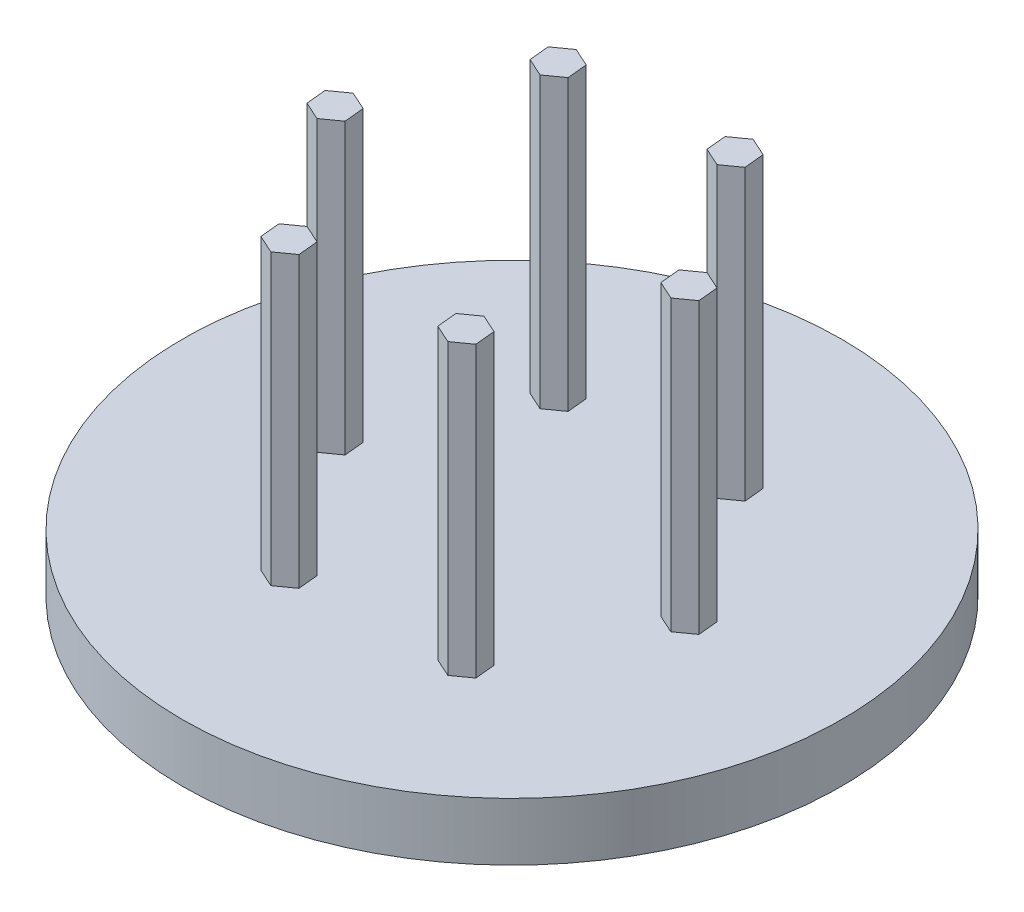
SolidWorks part; units mm, degrees
ref_plane "前视基准面" through (0, 0, 0) normal (0, 0, 1) x (1, 0, 0)
ref_plane "上视基准面" through (0, 0, 0) normal (0, 1, 0) x (1, 0, 0)
ref_plane "右视基准面" through (0, 0, 0) normal (1, 0, 0) x (0, 0, -1)
other "Configuration Table"
sketch "草图1" plane through (0, 0, 0) normal (0, 1, 0) x (1, 0, 0)
  line L0 (15.9541, 0.2119) -> (15.7851, 1.9437)
  line L1 (6.5472, 11.1786) -> (7.9625, 12.1908)
  line L2 (7.9625, 12.1908) -> (7.7935, 13.9226)
  line L3 (7.7935, 13.9226) -> (6.2093, 14.6422)
  line L4 (6.2093, 14.6422) -> (4.794, 13.63)
  line L5 (4.794, 13.63) -> (4.963, 11.8982)
  line L6 (4.963, 11.8982) -> (6.5472, 11.1786)
  line L7 (14.5388, -0.8003) -> (15.9541, 0.2119)
  line L8 (12.9546, -0.0807) -> (14.5388, -0.8003)
  line L9 (12.7856, 1.651) -> (12.9546, -0.0807)
  line L10 (14.2009, 2.6632) -> (12.7856, 1.651)
  line L11 (15.7851, 1.9437) -> (14.2009, 2.6632)
  line L12 (8.1605, -13.7107) -> (9.5758, -12.6985)
  line L13 (6.5763, -12.9911) -> (8.1605, -13.7107)
  line L14 (6.4074, -11.2593) -> (6.5763, -12.9911)
  line L15 (7.8226, -10.2471) -> (6.4074, -11.2593)
  line L16 (9.4069, -10.9667) -> (7.8226, -10.2471)
  line L17 (9.5758, -12.6985) -> (9.4069, -10.9667)
  line L18 (-7.7935, -13.9226) -> (-6.2093, -14.6422)
  line L19 (-7.9625, -12.1908) -> (-7.7935, -13.9226)
  line L20 (-6.5472, -11.1786) -> (-7.9625, -12.1908)
  line L21 (-4.963, -11.8982) -> (-6.5472, -11.1786)
  line L22 (-4.794, -13.63) -> (-4.963, -11.8982)
  line L23 (-6.2093, -14.6422) -> (-4.794, -13.63)
  line L24 (-15.9541, -0.2119) -> (-15.7851, -1.9437)
  line L25 (-14.5388, 0.8003) -> (-15.9541, -0.2119)
  line L26 (-12.9546, 0.0807) -> (-14.5388, 0.8003)
  line L27 (-12.7856, -1.651) -> (-12.9546, 0.0807)
  line L28 (-14.2009, -2.6632) -> (-12.7856, -1.651)
  line L29 (-15.7851, -1.9437) -> (-14.2009, -2.6632)
  line L30 (-8.1605, 13.7107) -> (-9.5758, 12.6985)
  line L31 (-6.5763, 12.9911) -> (-8.1605, 13.7107)
  line L32 (-6.4074, 11.2593) -> (-6.5763, 12.9911)
  line L33 (-7.8226, 10.2471) -> (-6.4074, 11.2593)
  line L34 (-9.4069, 10.9667) -> (-7.8226, 10.2471)
  line L35 (-9.5758, 12.6985) -> (-9.4069, 10.9667)
  circle A0 centre (0, 0) radius 28.5
  circle A1 centre (6.3783, 12.9104) radius 1.5069 construction
  point P3 (6.3783, 12.9104)
  point P45 (0, 0)
  dimension "D1" = 57
  dimension "D2" = 14.4
  dimension "D3" = 1.74
  dimension "D4" = 6
ref_plane "基准面1" through (0, 0, 0) normal (0, 1, 0) x (1, 0, 0)
sketch "草图2" plane through (0, 0, 0) normal (0, 1, 0) x (1, 0, 0)
  circle A0 centre (0, 0) radius 28.5 construction
  circle A1 centre (0, 0) radius 28.5
extrude "凸台-拉伸1" add sketch "草图1" along normal blind 25 contours L5 L6 L1 L2 L3 L4 | L0 L11 L10 L9 L8 L7 | L12 L17 L16 L15 L14 L13 | L18 L23 L22 L21 L20 L19 | L27 L26 L25 L24 L29 L28 | L31 L30 L35 L34 L33 L32
extrude "凸台-拉伸2" add sketch "草图2" against normal blind 5
sketch "草图3" plane through (0, -5, 0) normal (0, -1, 0) x (-1, 0, 0)
  line L0 (6.0671, 3.7132) -> (8.6033, 2.3344)
  line L7 (0, -7.1132) -> (-2.5, -8.5566)
  line L8 (-2.5, -8.5566) -> (-2.5, -11.4434)
  line L9 (-2.5, -11.4434) -> (0, -12.8868)
  line L10 (0, -12.8868) -> (2.5, -11.4434)
  line L11 (2.5, -11.4434) -> (2.5, -8.5566)
  line L12 (2.5, -8.5566) -> (0, -7.1132)
  line L13 (8.6033, 2.3344) -> (11.0655, 3.8413)
  line L14 (11.0655, 3.8413) -> (10.9915, 6.7271)
  line L15 (10.9915, 6.7271) -> (8.4554, 8.106)
  line L16 (8.4554, 8.106) -> (5.9932, 6.5991)
  line L17 (5.9932, 6.5991) -> (6.0671, 3.7132)
  line L18 (-6.3343, 3.2365) -> (-6.4822, 6.1194)
  line L19 (-6.4822, 6.1194) -> (-9.0528, 7.4329)
  line L20 (-9.0528, 7.4329) -> (-11.4756, 5.8634)
  line L21 (-11.4756, 5.8634) -> (-11.3278, 2.9804)
  line L22 (-11.3278, 2.9804) -> (-8.7571, 1.667)
  line L23 (-8.7571, 1.667) -> (-6.3343, 3.2365)
  circle A0 centre (0, -10) radius 2.5 construction
  point P24 (0, 0)
  dimension "D1" = 5
  dimension "D2" = 10
  dimension "D3" = 3
extrude "凸台-拉伸4" add sketch "草图3" along normal blind 5
